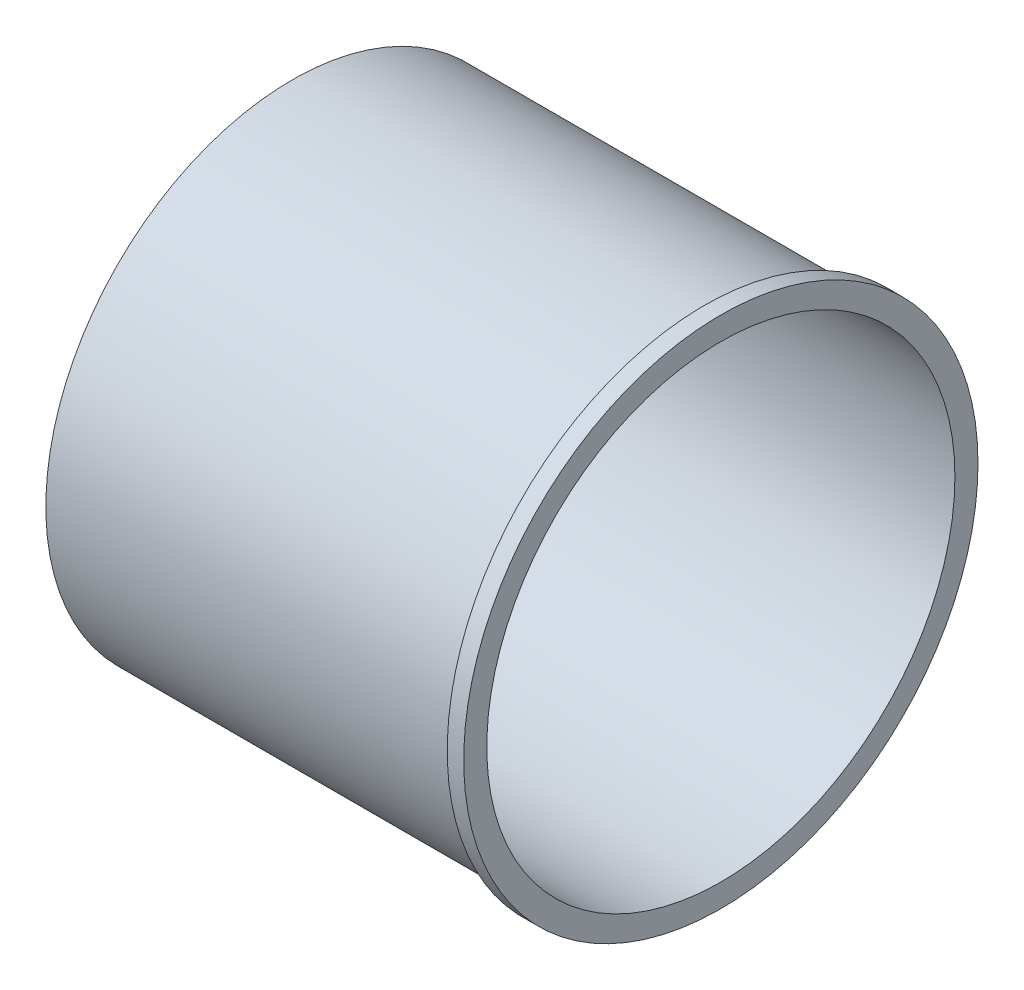
SolidWorks part; units mm, degrees
ref_plane "Front Plane" through (0, 0, 0) normal (1, 0, 0) x (0, 1, 0)
ref_plane "Top Plane" through (0, 0, 0) normal (0, 0, 1) x (0, 1, 0)
ref_plane "Right Plane" through (0, 0, 0) normal (0, 1, 0) x (-1, 0, 0)
sketch "Sketch1" plane through (0, 0, 0) normal (1, 0, 0) x (0, 1, 0)
  circle A0 centre (0, 0) radius 37.973
  circle A1 centre (0, 0) radius 36.068
  dimension "D1" = 75.946
  dimension "D2" = 1.905
extrude "Boss-Extrude1" add sketch "Sketch1" along normal blind 63.5
sketch "Sketch2" plane through (63.5, 0, 0) normal (1, 0, 0) x (0, 1, 0)
  circle A0 centre (0, 0) radius 36.068 construction
  circle A1 centre (0, 0) radius 36.068
  circle A2 centre (0, 0) radius 39.624
  dimension "D1" = 79.248
extrude "Boss-Extrude2" add sketch "Sketch2" along normal blind 2.54
